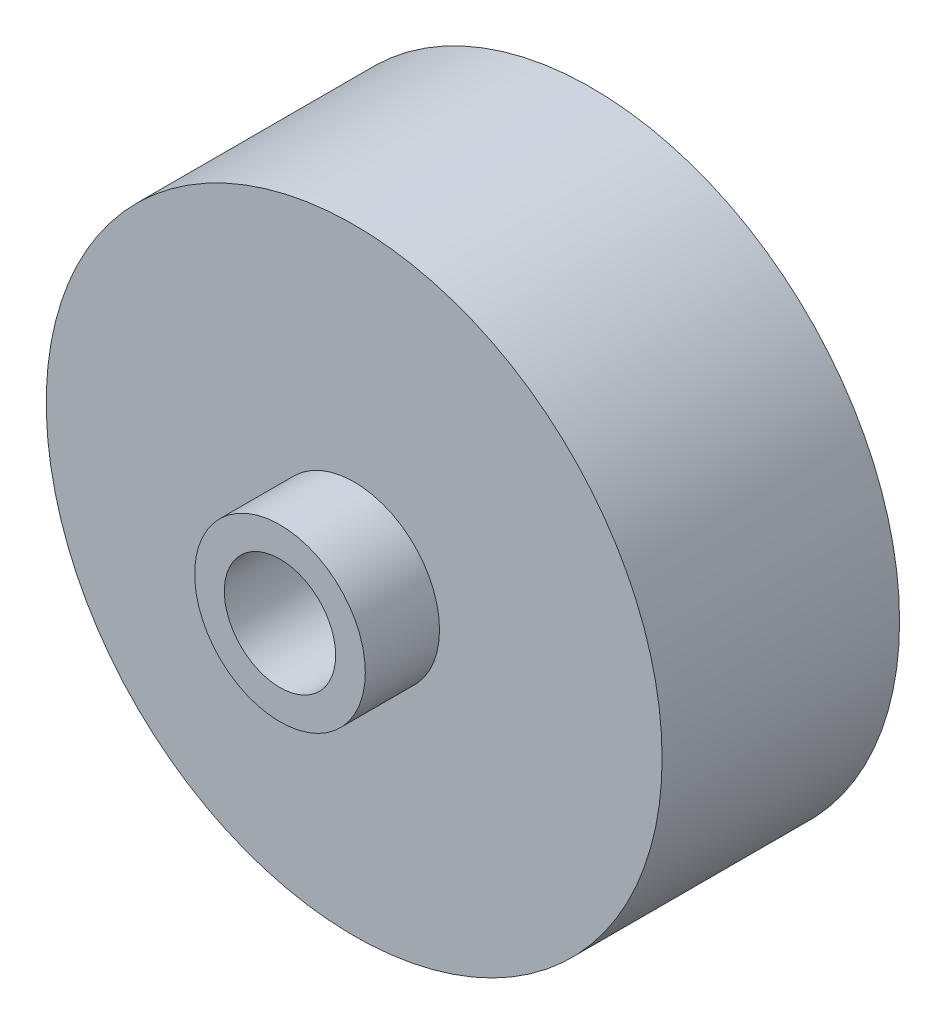
SolidWorks part; units mm, degrees
material "Настроенная пользователем пластмасса"
ref_plane "Спереди" through (0, 0, 0) normal (0, 0, 1) x (1, 0, 0)
ref_plane "Сверху" through (0, 0, 0) normal (0, 1, 0) x (1, 0, 0)
ref_plane "Справа" through (0, 0, 0) normal (1, 0, 0) x (0, 0, -1)
sketch "Эскиз1" plane through (0, 0, 0) normal (0, 1, 0) x (1, 0, 0)
  line L0 (3.75, -21) -> (5.75, -21)
  line L1 (5.75, -21) -> (5.75, -16)
  line L2 (5.75, -16) -> (20.75, -16)
  line L3 (20.75, -16) -> (20.75, 0)
  line L4 (20.75, 0) -> (3.75, 0)
  line L5 (3.75, 0) -> (3.75, -21)
  line L6 (0, 0) -> (0, -21) construction
revolve "Повернуть1" add sketch "Эскиз1" angle 360 about L6
